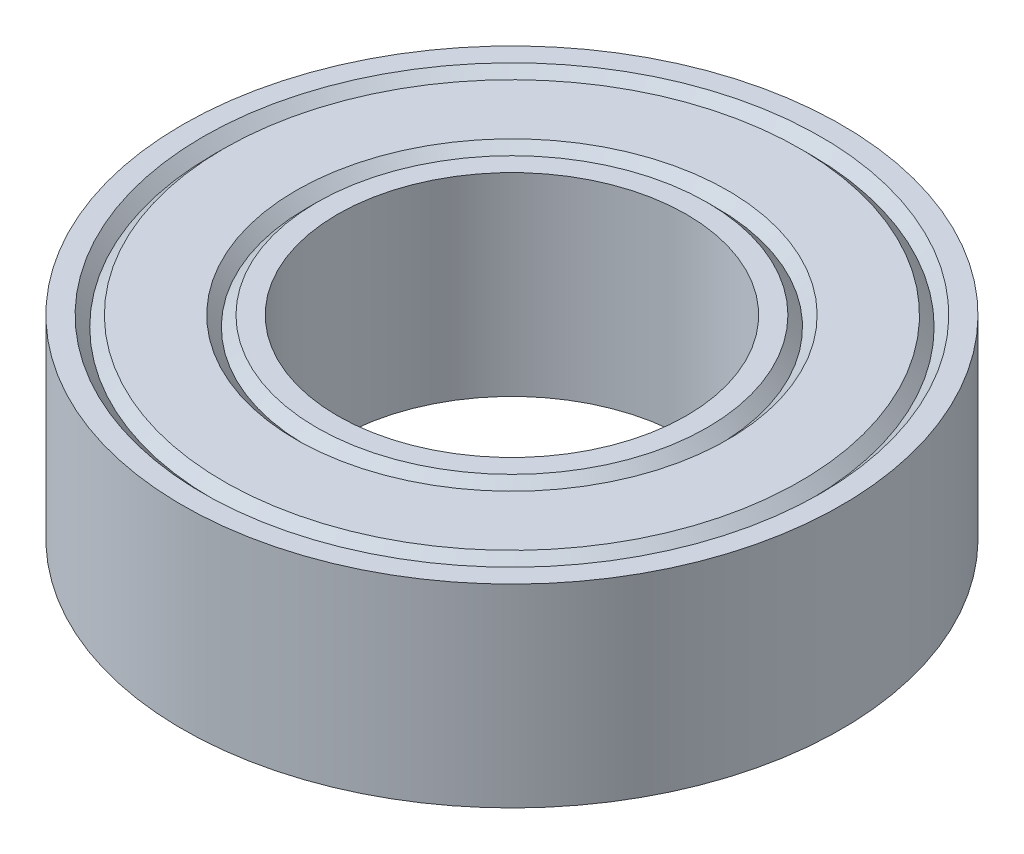
SolidWorks part; units mm, degrees
ref_plane "Front Plane" through (0, 0, 0) normal (0, 0, 1) x (1, 0, 0)
ref_plane "Top Plane" through (0, 0, 0) normal (0, 1, 0) x (1, 0, 0)
ref_plane "Right Plane" through (0, 0, 0) normal (1, 0, 0) x (0, 0, -1)
sketch "Sketch1" plane through (0, 0, 0) normal (0, 0, 1) x (1, 0, 0)
  line L0 (0, 2.5) -> (0, -2.5) construction
  line L1 (-4.5, 2.5) -> (-5.0333, 2.5)
  line L2 (-4.5, 2.5) -> (-4.5, -2.5)
  line L3 (-4.5, -2.5) -> (-5.0333, -2.5)
  line L4 (-8.5, 2.5) -> (-8.5, -2.5)
  line L5 (-7.9667, 2.5) -> (-7.7, 2.2333)
  line L6 (-7.7, 2.2333) -> (-7.4333, 2.5)
  line L7 (-5.5667, 2.5) -> (-5.3, 2.2333)
  line L8 (-5.3, 2.2333) -> (-5.0333, 2.5)
  line L9 (-7.9667, -2.5) -> (-7.7, -2.2333)
  line L10 (-7.7, -2.2333) -> (-7.4333, -2.5)
  line L11 (-5.5667, -2.5) -> (-5.3, -2.2333)
  line L12 (-5.3, -2.2333) -> (-5.0333, -2.5)
  line L13 (-5.5667, -2.5) -> (-7.4333, -2.5)
  line L14 (-7.9667, -2.5) -> (-8.5, -2.5)
  line L15 (-7.9667, 2.5) -> (-8.5, 2.5)
  line L16 (-5.5667, 2.5) -> (-7.4333, 2.5)
  line L17 (-7.7, 2.2333) -> (-5.3, 2.2333) construction
  line L18 (-7.7, 2.2333) -> (-7.7, -2.2333) construction
  line L19 (-5.3, -2.2333) -> (-7.7, -2.2333) construction
  line L20 (-5.3, 2.2333) -> (-5.3, -2.2333) construction
  line L21 (-7.7, 0) -> (-6.9, 0) construction
  line L22 (-5.0333, 2.5) -> (-5.5667, 2.5) construction
  line L23 (-6.9, 0) -> (-6.1, 0) construction
  line L24 (-7.7, 0) -> (-8.5, 0) construction
  line L25 (-6.1, 0) -> (-5.3, 0) construction
  line L26 (-5.3, 0) -> (-4.5, 0) construction
  dimension "D1" = 5
  dimension "D2" = 9
  dimension "D3" = 17
revolve "Revolve1" add sketch "Sketch1" angle 360 about L0
